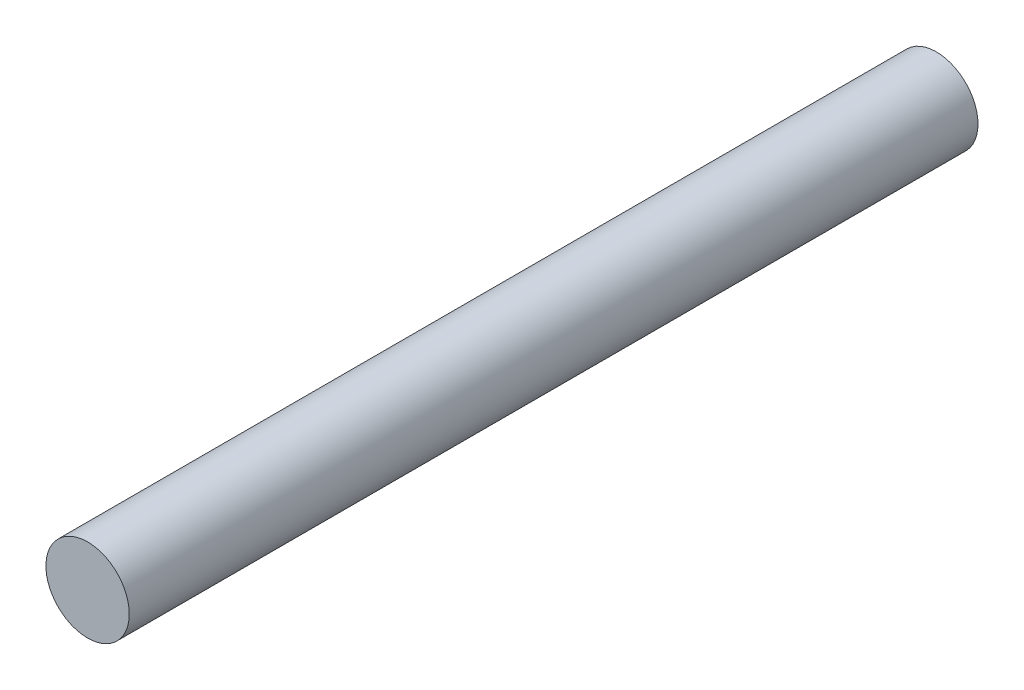
SolidWorks part; units mm, degrees
material "ASTM A36 Steel"
ref_plane "Front Plane" through (0, 0, 0) normal (0, 0, 1) x (1, 0, 0)
ref_plane "Top Plane" through (0, 0, 0) normal (0, 1, 0) x (1, 0, 0)
ref_plane "Right Plane" through (0, 0, 0) normal (1, 0, 0) x (0, 0, -1)
sketch "Sketch1" plane through (0, 0, 0) normal (0, 0, 1) x (1, 0, 0)
  circle A0 centre (0, 0) radius 5
  dimension "D1" = 10
extrude "Boss-Extrude1" add sketch "Sketch1" along normal blind 101.85
